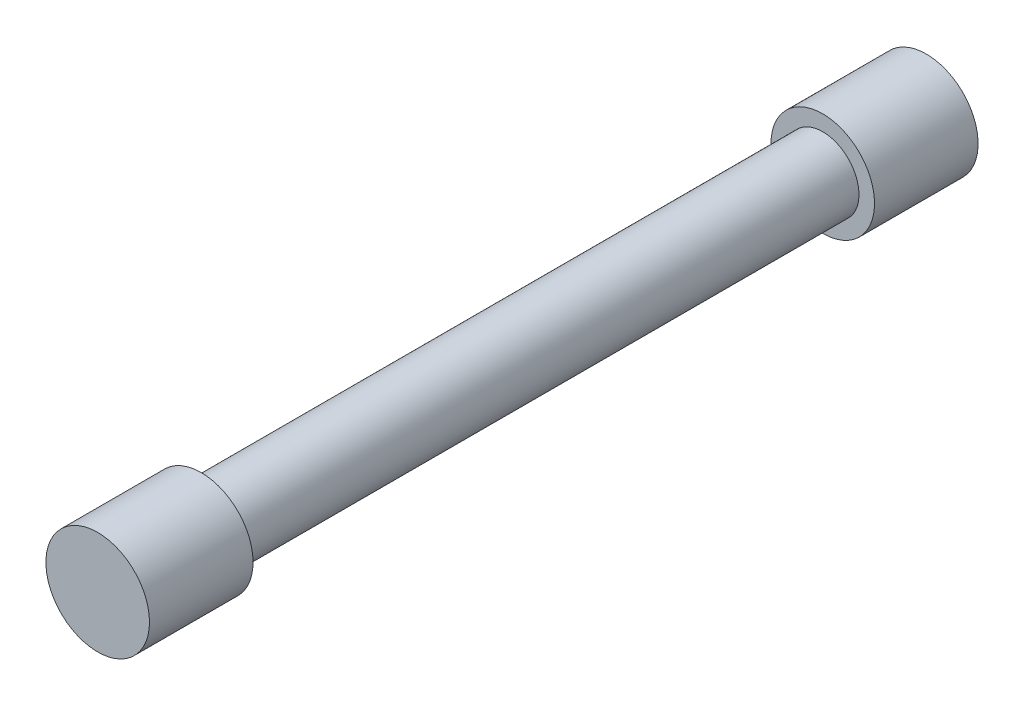
SolidWorks part; units mm, degrees
material "1023 Carbon Steel Sheet (SS)"
ref_plane "Front Plane" through (0, 0, 0) normal (0, 0, 1) x (1, 0, 0)
ref_plane "Top Plane" through (0, 0, 0) normal (0, 1, 0) x (1, 0, 0)
ref_plane "Right Plane" through (0, 0, 0) normal (1, 0, 0) x (0, 0, -1)
sketch "Sketch1" plane through (0, 0, 0) normal (0, 0, 1) x (1, 0, 0)
  circle A0 centre (0, 0) radius 2.2225
  dimension "D1" = 4.445
extrude "Boss-Extrude1" add sketch "Sketch1" along normal blind 38.1
sketch "Sketch2" plane through (0, 0, 0) normal (0, 0, -1) x (-1, 0, 0)
  circle A0 centre (0, 0) radius 3.175
  dimension "D1" = 6.35
extrude "Boss-Extrude2" add sketch "Sketch2" along normal blind 6.35
sketch "Sketch3" plane through (0, 0, 38.1) normal (0, 0, 1) x (1, 0, 0)
  circle A0 centre (0, 0) radius 3.175
extrude "Boss-Extrude3" add sketch "Sketch3" along normal blind 6.35
